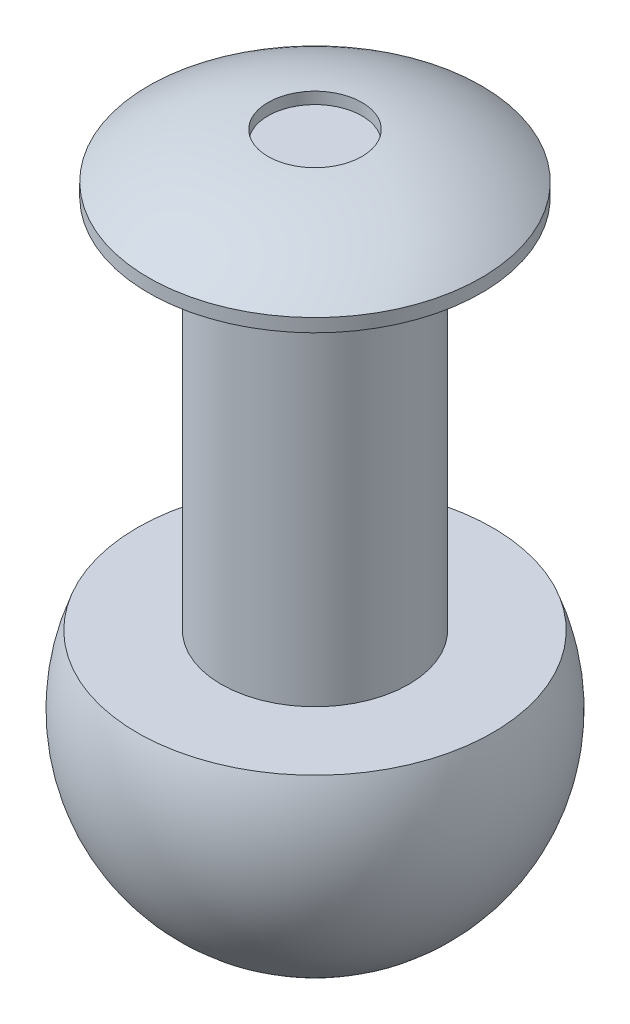
SolidWorks part; units mm, degrees
ref_plane "Front Plane" through (0, 0, 0) normal (0, 0, 1) x (1, 0, 0)
ref_plane "Top Plane" through (0, 0, 0) normal (0, 1, 0) x (1, 0, 0)
ref_plane "Right Plane" through (0, 0, 0) normal (1, 0, 0) x (0, 0, -1)
sketch "Sketch1" plane through (0, 0, 0) normal (0, 1, 0) x (1, 0, 0)
  circle A0 centre (0, 0) radius 2
extrude "Boss-Extrude1" add sketch "Sketch1" along normal blind 8
sketch "Sketch2" plane through (0, 0, 0) normal (0, 0, 1) x (1, 0, 0)
  line L0 (0, 0) -> (0, -5.5121)
  line L1 (0, 0) -> (-3.7882, 0)
  line L2 (-3.7882, 0) -> (0, 0)
  arc A0 (-3.7882, 0) -> (0, -5.5121) centre (0, -1.4543) ccw
revolve "Revolve1" add sketch "Sketch2" angle 360 about L0
sketch "Sketch3" plane through (0, 0, 0) normal (0, 0, 1) x (1, 0, 0)
  line L0 (0, 8) -> (0, 9.2279)
  line L1 (2, 8) -> (-2, 8) construction
  line L2 (0, 8) -> (-3.5474, 8)
  line L3 (-3.5474, 8) -> (0, 8)
  line L4 (-3.5474, 8) -> (-3.5474, 8.2816)
  arc A0 (-3.5474, 8.2816) -> (0, 9.2279) centre (-0.5962, 4.3404) cw
revolve "Revolve2" add sketch "Sketch3" angle 360 about L0
sketch "Sketch4" plane through (0, 0, 0) normal (0, 1, 0) x (1, 0, 0)
  circle A0 centre (0, 0) radius 1
extrude "Cut-Extrude1" cut sketch "Sketch4" against normal blind 2 from offset 11
